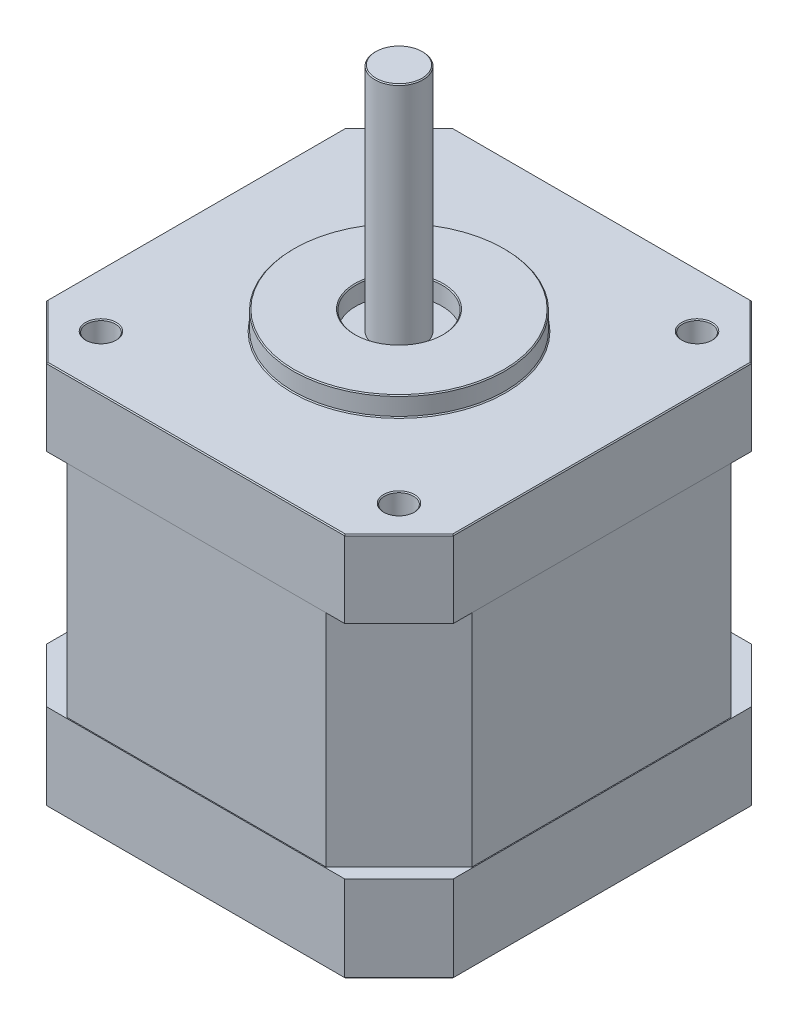
SolidWorks part; units mm, degrees
ref_plane "Front Plane" through (0, 0, 0) normal (0, 0, 1) x (1, 0, 0)
ref_plane "Top Plane" through (0, 0, 0) normal (0, 1, 0) x (1, 0, 0)
ref_plane "Right Plane" through (0, 0, 0) normal (1, 0, 0) x (0, 0, -1)
sketch "Sketch1" plane through (0, 0, 0) normal (0, 1, 0) x (1, 0, 0)
  line L0 (0, 0) -> (-12.9419, 0) construction
  line L1 (-15.5, -21.15) -> (15.5, -21.15)
  line L2 (-21.15, -15.5) -> (-21.15, 15.5)
  line L3 (-15.5, 21.15) -> (15.5, 21.15)
  line L4 (21.15, -15.5) -> (21.15, 15.5)
  line L5 (-21.15, -21.15) -> (21.15, 21.15) construction
  line L6 (-21.15, 21.15) -> (21.15, -21.15) construction
  line L7 (-21.15, 15.5) -> (-15.5, 21.15)
  line L8 (15.5, 21.15) -> (21.15, 15.5)
  line L9 (15.5, -21.15) -> (21.15, -15.5)
  line L10 (-21.15, -15.5) -> (-15.5, -21.15)
  circle A0 centre (-15.5, 15.5) radius 1.5
  circle A1 centre (15.5, -15.5) radius 1.5
  circle A2 centre (15.5, 15.5) radius 1.5
  circle A3 centre (-15.5, -15.5) radius 1.5
  point P0 (0, 0)
  dimension "D3" = 3
  dimension "D1" = 42.3
  dimension "D2" = 31
extrude "Boss-Extrude1" add sketch "Sketch1" along normal blind 9
sketch "Sketch4" plane through (0, 9, 0) normal (0, 1, 0) x (1, 0, 0)
  line L24 (13.4787, 21.05) -> (-13.4787, 21.05)
  line L25 (-21.05, 13.4787) -> (-21.05, -13.4787)
  line L26 (-13.4787, -21.05) -> (13.4787, -21.05)
  line L27 (21.05, -13.4787) -> (21.05, 13.4787)
  line L28 (-21.05, 13.4787) -> (-13.4787, 21.05)
  line L29 (-15.5, 21.15) -> (-21.15, 15.5) construction
  line L30 (13.4787, 21.05) -> (21.05, 13.4787)
  line L31 (21.05, -13.4787) -> (13.4787, -21.05)
  line L32 (-13.4787, -21.05) -> (-21.05, -13.4787)
  circle A0 centre (-15.5, 15.5) radius 1.5 construction
  circle A1 centre (15.5, 15.5) radius 1.5 construction
  circle A2 centre (15.5, -15.5) radius 1.5 construction
  circle A3 centre (-15.5, -15.5) radius 1.5 construction
  circle A4 centre (-15.5, 15.5) radius 1.5
  circle A5 centre (15.5, 15.5) radius 1.5
  circle A6 centre (15.5, -15.5) radius 1.5
  circle A7 centre (-15.5, -15.5) radius 1.5
  point P41 (0, 0)
  dimension "D2" = 1.5
  dimension "D3" = 4
extrude "Boss-Extrude4" add sketch "Sketch4" along normal blind 23
sketch "Sketch5" plane through (0, 32, 0) normal (0, 1, 0) x (1, 0, 0)
  line L9 (-15.5, 21.15) -> (-21.15, 15.5)
  line L10 (-21.15, 15.5) -> (-21.15, -15.5)
  line L11 (-21.15, -15.5) -> (-15.5, -21.15)
  line L12 (-15.5, -21.15) -> (15.5, -21.15)
  line L13 (15.5, -21.15) -> (21.15, -15.5)
  line L14 (21.15, -15.5) -> (21.15, 15.5)
  line L15 (21.15, 15.5) -> (15.5, 21.15)
  line L16 (15.5, 21.15) -> (-15.5, 21.15)
  line L17 (-15.5, 21.15) -> (-21.15, 15.5)
  line L18 (-21.15, 15.5) -> (-21.15, -15.5)
  line L19 (-21.15, -15.5) -> (-15.5, -21.15)
  line L20 (-15.5, -21.15) -> (15.5, -21.15)
  line L21 (15.5, -21.15) -> (21.15, -15.5)
  line L22 (21.15, -15.5) -> (21.15, 15.5)
  line L23 (21.15, 15.5) -> (15.5, 21.15)
  line L24 (15.5, 21.15) -> (-15.5, 21.15)
  circle A0 centre (15.5, 15.5) radius 1.5 construction
  circle A1 centre (-15.5, 15.5) radius 1.5 construction
  circle A2 centre (-15.5, -15.5) radius 1.5 construction
  circle A3 centre (15.5, -15.5) radius 1.5 construction
  circle A4 centre (15.5, 15.5) radius 1.5
  circle A5 centre (-15.5, 15.5) radius 1.5
  circle A6 centre (-15.5, -15.5) radius 1.5
  circle A7 centre (15.5, -15.5) radius 1.5
  dimension "D1" = 0
extrude "Boss-Extrude6" add sketch "Sketch5" along normal blind 8
sketch "Sketch2" plane through (0, 40, 0) normal (0, 1, 0) x (1, 0, 0)
  circle A0 centre (0, 0) radius 11
  circle A1 centre (0, 0) radius 4.5
  dimension "D1" = 22
  dimension "D2" = 9
extrude "Boss-Extrude2" add sketch "Sketch2" along normal blind 2
sketch "Sketch3" plane through (0, 40, 0) normal (0, 1, 0) x (1, 0, 0)
  circle A0 centre (0, 0) radius 2.5
  dimension "D1" = 5
extrude "Boss-Extrude3" add sketch "Sketch3" along normal offset from surface (24 mm away) 22 separate body up to face at (0, 42, 11) offset beyond the face yes
chamfer "Chamfer1" distance 0.1 angle 45 27 edges at (-15.5, 0, 14) (15.5, 0, 14) (-21.15, 0, 0) (-18.325, 0, 18.325) (0, 0, 21.15) (18.325, 0, 18.325) (21.15, 0, 0) (18.325, 0, -18.325) (0, 0, -21.15) (-18.325, 0, -18.325) (-15.5, 0, -14) (15.5, 0, -14) (0, 40, 11) (15.5, 40, 17) (-15.5, 40, -14) (18.325, 40, -18.325) (21.15, 40, 0) (18.325, 40, 18.325) (0, 40, 21.15) (-18.325, 40, 18.325) (-21.15, 40, 0) (-18.325, 40, -18.325) (0, 40, -21.15) (15.5, 40, -14) (-15.5, 40, 17) (0, 42, 4.5) (0, 42, 11)
chamfer "Chamfer2" distance 0.1 angle 45 1 edges at (0, 64, 2.5)
